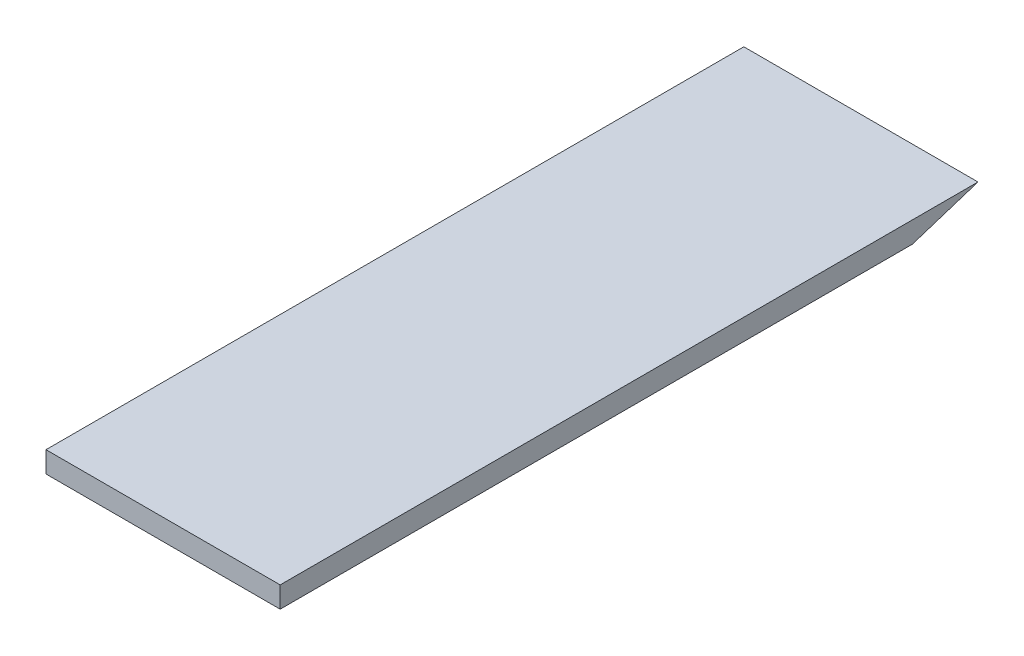
SolidWorks part; units mm, degrees
ref_plane "Front Plane" through (0, 0, 0) normal (0, 0, 1) x (1, 0, 0)
ref_plane "Top Plane" through (0, 0, 0) normal (0, 1, 0) x (1, 0, 0)
ref_plane "Right Plane" through (0, 0, 0) normal (1, 0, 0) x (0, 0, -1)
sketch "Sketch1" plane through (0, 0, 0) normal (1, 0, 0) x (0, 0, -1)
  line L19 (0, 9) -> (0, 0)
  line L20 (0, 0) -> (270, 0)
  line L21 (270, 0) -> (298, 9)
  line L37 (0, 9) -> (298, 9)
  point P13 (0, 0)
  point P23 (0, 0)
  dimension "D1" = 9
  dimension "D8" = 28
  dimension "D9" = 270
extrude "Boss-Extrude1" add sketch "Sketch1" along normal blind 100 contours L19 L20 L21 L37
